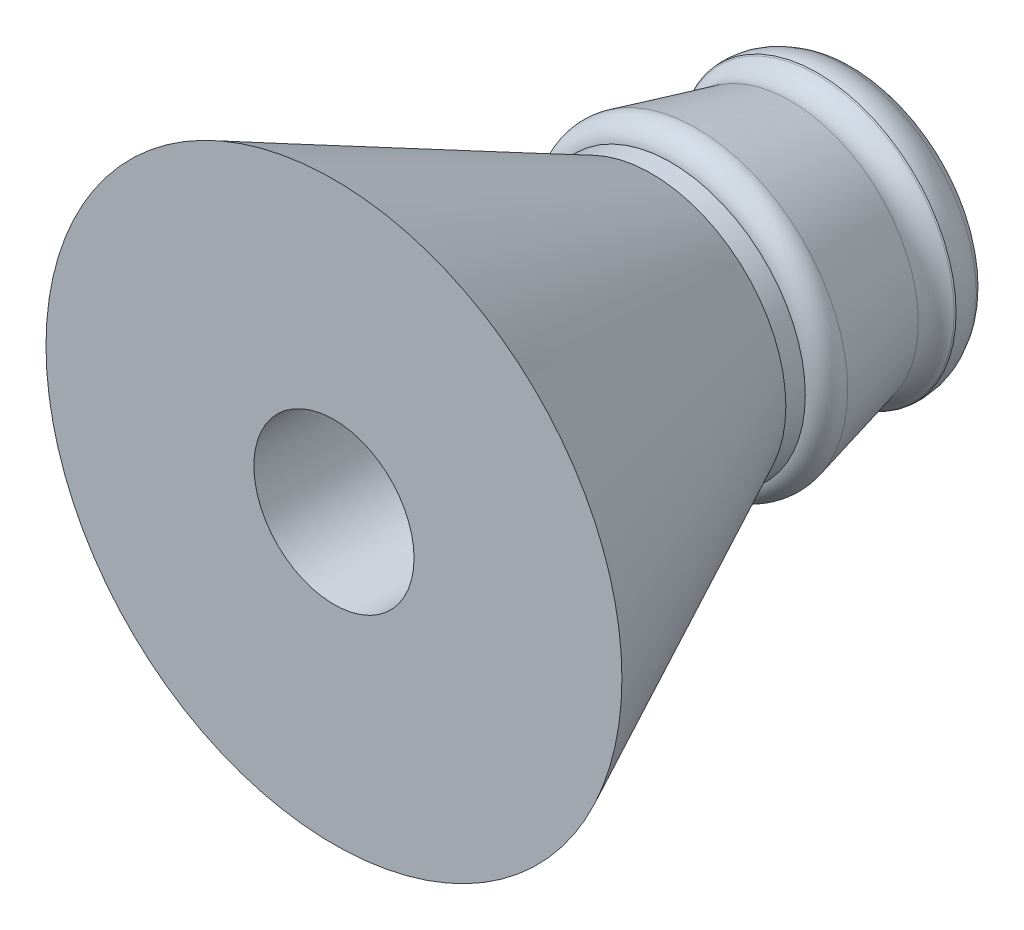
SolidWorks part; units mm, degrees
ref_plane "Front Plane" through (0, 0, 0) normal (0, 0, 1) x (1, 0, 0)
ref_plane "Top Plane" through (0, 0, 0) normal (0, 1, 0) x (1, 0, 0)
ref_plane "Right Plane" through (0, 0, 0) normal (1, 0, 0) x (0, 0, -1)
sketch "Sketch1" plane through (0, 0, 0) normal (0, 1, 0) x (1, 0, 0)
  line L0 (-3043.8147, -632.5673) -> (-3043.8147, -614.5673) construction
  line L1 (0, 0) -> (0, 21.2766) construction
  line L2 (-7.75, 0) -> (-7.75, 3.5987)
  line L3 (-13, 0) -> (-13, 1.8822)
  line L4 (-14.6406, 4.3433) -> (-12.3713, 13.4467)
  line L5 (-10.6246, 19.9773) -> (-9.75, 19.9773)
  line L6 (-9.25, 19.4773) -> (-9.25, 14.4132)
  line L7 (-7.75, 0) -> (-13, 0) construction
  line L8 (-7.75, 0) -> (-7.75, -30.7253)
  line L9 (-7.75, -30.7253) -> (-27.8635, -30.7253)
  line L10 (-27.8635, -30.7253) -> (-13, 0)
  arc A0 (-13, 1.8822) -> (-14.6406, 4.3433) centre (-12.7, 3.8596) cw
  arc A1 (-12.3713, 13.4467) -> (-13.3009, 15.9773) centre (-14.7, 14.0273) ccw
  arc A2 (-13.3009, 15.9773) -> (-13.4, 16.0713) centre (-13.0094, 16.3835) cw
  arc A3 (-10.6246, 19.9773) -> (-12.7439, 18.7034) centre (-10.6246, 17.5773) ccw
  arc A4 (-9.75, 19.9773) -> (-9.25, 19.4773) centre (-9.75, 19.4773) cw
  arc A5 (-9.25, 14.4132) -> (-7.75, 3.5987) centre (2.698, 10.5592) ccw
  arc A6 (-12.7439, 18.7034) -> (-13.4, 16.0713) centre (-9.4206, 16.4773) ccw
  point P22 (-14.7, 3.8596)
  point P23 (-12.3, 14.0273)
  dimension "D4" = 2
  dimension "D5" = 2.4
  dimension "D6" = 0.5
  dimension "D7" = 4
  dimension "D8" = 0.5
  dimension "D10" = 2.4
  dimension "D18" = 19.9773
  dimension "D19" = 25.4879
  dimension "D22" = 12.5542
  dimension "D1" = 18
  dimension "D2" = 15.5
  dimension "D3" = 26
  dimension "D9" = 5.95
  dimension "D11" = 4
  dimension "D12" = 26.8
  dimension "D13" = 18.5
  dimension "D14" = 19.5
  dimension "D15" = 29.4
  dimension "D16" = 1.1
  dimension "D17" = 0.5
  dimension "D20" = 1.8822
  dimension "D21" = 5.0641
  dimension "D23" = 3.5987
revolve "Revolve1" add sketch "Sketch1" angle 360 about L1
